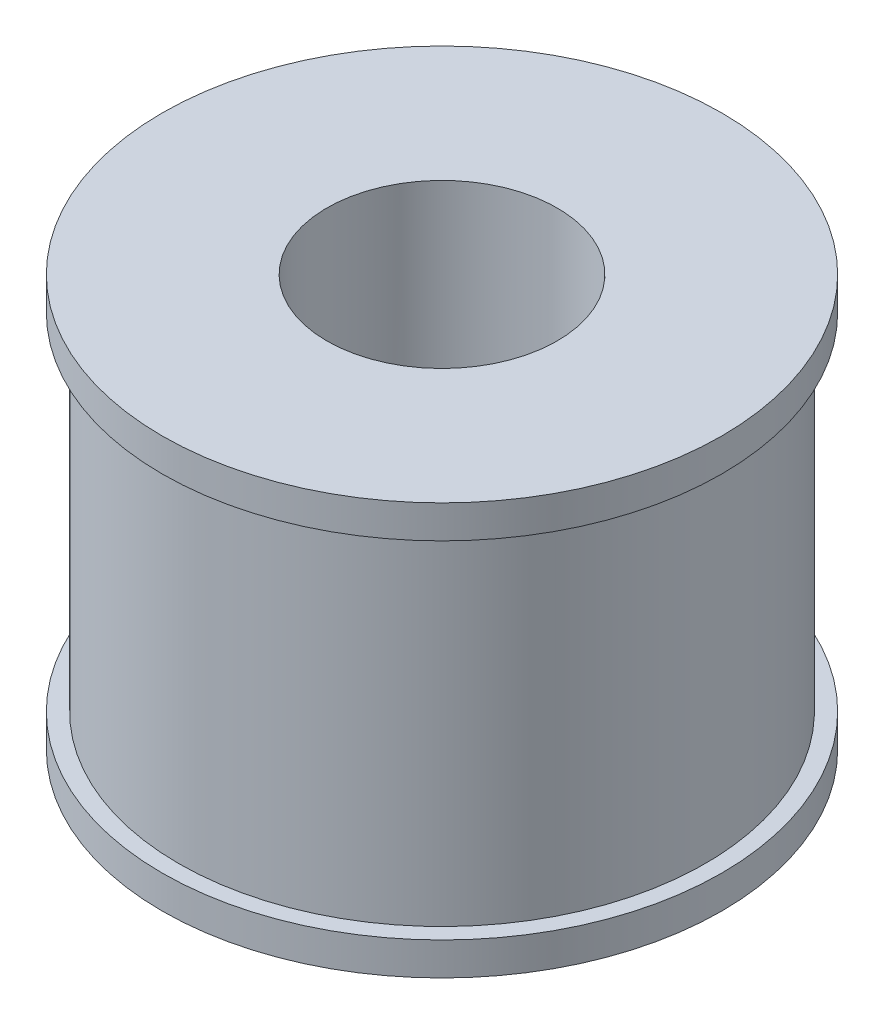
SolidWorks part; units mm, degrees
ref_plane "Alzado" through (0, 0, 0) normal (0, 0, 1) x (1, 0, 0)
ref_plane "Planta" through (0, 0, 0) normal (0, 1, 0) x (1, 0, 0)
ref_plane "Vista lateral" through (0, 0, 0) normal (1, 0, 0) x (0, 0, -1)
sketch "Croquis1" plane through (0, 0, 0) normal (0, 1, 0) x (1, 0, 0)
  circle A0 centre (0, 0) radius 3
  circle A1 centre (0, 0) radius 15
  dimension "D1" = 6
  dimension "D2" = 30
extrude "Saliente-Extruir1" add sketch "Croquis1" along normal blind 25
sketch "Croquis2" plane through (0, 0, 0) normal (0, -1, 0) x (1, 0, 0)
  circle A0 centre (0, 0) radius 3
  circle A1 centre (0, 0) radius 16.5
  dimension "D1" = 33
extrude "Saliente-Extruir2" add sketch "Croquis2" against normal blind 2
sketch "Croquis3" plane through (0, 25, 0) normal (0, 1, 0) x (1, 0, 0)
  circle A0 centre (0, 0) radius 3
  circle A1 centre (0, 0) radius 16.5
  dimension "D1" = 33
extrude "Saliente-Extruir3" add sketch "Croquis3" against normal blind 2
sketch "Croquis4" plane through (0, 0, 0) normal (0, 0, 1) x (1, 0, 0)
  line L2 (-16.5, 0) -> (16.5, 0) construction
  circle A0 centre (0, 5) radius 1.625
  dimension "D1" = 3.25
  dimension "D2" = 5
extrude "Cortar-Extruir1" cut sketch "Croquis4" against normal up to next
sketch "Croquis5" plane through (0, 25, 0) normal (0, 1, 0) x (1, 0, 0)
  circle A0 centre (0, 0) radius 7
  dimension "D1" = 14
extrude "Cortar-Extruir2" cut sketch "Croquis5" against normal blind 16
sketch "Croquis7" plane through (0, 0, 0) normal (0, -1, 0) x (1, 0, 0)
  line L3 (0, -3) -> (0, -4.5) construction
  line L4 (-3.17, -7.5) -> (3.17, -7.5)
  line L5 (0, -4.5) -> (-3.17, -4.5)
  line L8 (-3.17, -4.5) -> (-3.17, -7.5)
  line L9 (3.17, -7.5) -> (3.17, -4.5)
  line L10 (3.17, -4.5) -> (0, -4.5)
  circle A1 centre (0, 0) radius 3 construction
  point P0 (0, 0)
  dimension "D1" = 3.17
  dimension "D2" = 4.5
  dimension "D3" = 7.5
extrude "Cortar-Extruir3" cut sketch "Croquis7" against normal blind 9
sketch "Croquis10" plane through (0, 23, 0) normal (0, -1, 0) x (1, 0, 0)
  line L0 (-15, 0) -> (-16, 0) construction
  circle A0 centre (0, 0) radius 15 construction
  circle A1 centre (0, 0) radius 16
  circle A2 centre (0, 0) radius 15
  circle A3 centre (0, 0) radius 16.5 construction
  dimension "D1" = 32
extrude "Saliente-Extruir5" add sketch "Croquis10" along normal blind 21
sketch "Croquis12" plane through (0, 2, 0) normal (0, 1, 0) x (1, 0, 0)
  line L0 (-16, 0) -> (-17, 0) construction
  circle A0 centre (0, 0) radius 16 construction
  circle A1 centre (0, 0) radius 17
  circle A2 centre (0, 0) radius 16
  circle A3 centre (0, 0) radius 16.5 construction
  dimension "D1" = 34
extrude "Saliente-Extruir6" add sketch "Croquis12" against normal blind 2
sketch "Croquis13" plane through (0, 23, 0) normal (0, -1, 0) x (1, 0, 0)
  line L0 (-16, 0) -> (-17, 0) construction
  circle A0 centre (0, 0) radius 16 construction
  circle A1 centre (0, 0) radius 16
  circle A2 centre (0, 0) radius 17
  circle A3 centre (0, 0) radius 16.5 construction
  dimension "D1" = 34
extrude "Saliente-Extruir7" add sketch "Croquis13" against normal blind 2
sketch "Croquis14" plane through (0, 0, 0) normal (0, -1, 0) x (1, 0, 0)
  circle A0 centre (0, 0) radius 3.1
  dimension "D1" = 6.2
extrude "Cortar-Extruir4" cut sketch "Croquis14" against normal blind 10
sketch "Croquis15" plane through (0, 0, -7.5) normal (0, 0, 1) x (1, 0, 0)
  circle A0 centre (0, 5) radius 1.625
extrude "Cortar-Extruir5" cut sketch "Croquis15" against normal blind 9
